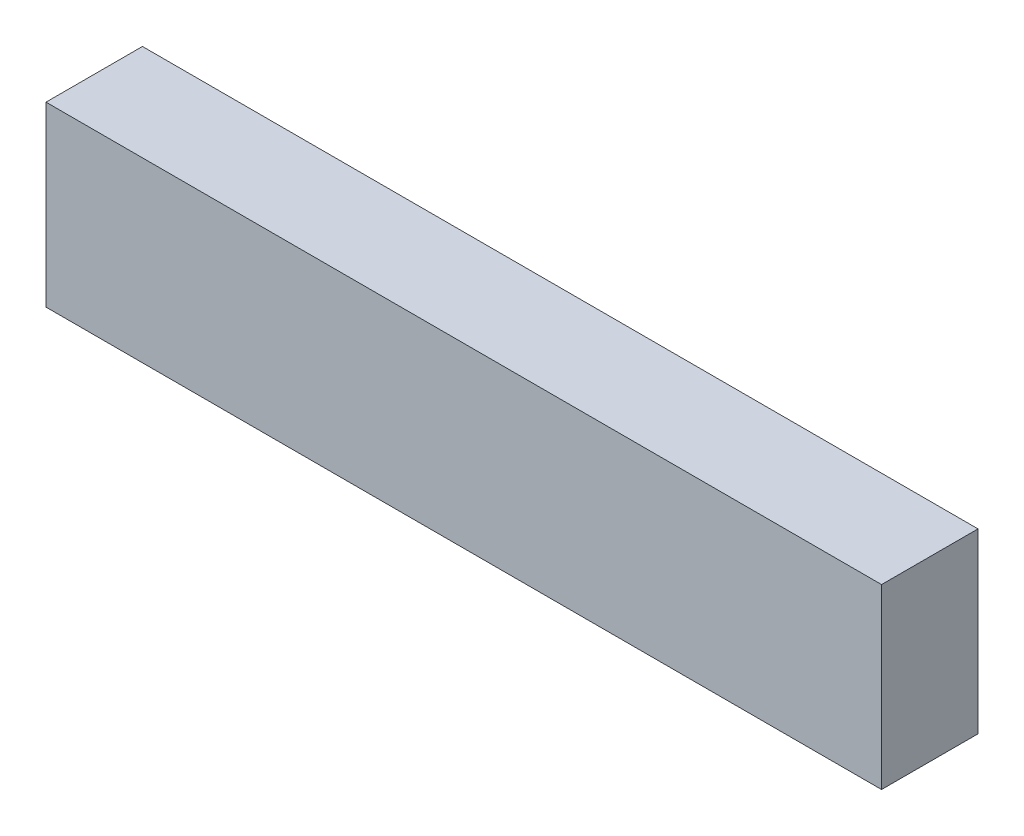
SolidWorks part; units mm, degrees
ref_plane "Front Plane" through (0, 0, 0) normal (0, 0, 1) x (1, 0, 0)
ref_plane "Top Plane" through (0, 0, 0) normal (0, 1, 0) x (1, 0, 0)
ref_plane "Right Plane" through (0, 0, 0) normal (1, 0, 0) x (0, 0, -1)
sketch "Sketch1" plane through (0, 0, 0) normal (0, 0, 1) x (1, 0, 0)
  line L5 (-62.6, -13.3) -> (62.6, -13.3)
  line L6 (-62.6, -13.3) -> (-62.6, 13.3)
  line L7 (-62.6, 13.3) -> (62.6, 13.3)
  line L8 (62.6, -13.3) -> (62.6, 13.3)
  line L9 (-62.6, -13.3) -> (62.6, 13.3) construction
  line L10 (-62.6, 13.3) -> (62.6, -13.3) construction
  point P0 (0, 0)
  dimension "D1" = 26.6
  dimension "D2" = 125.2
extrude "Boss-Extrude1" add sketch "Sketch1" along normal blind 14.45
